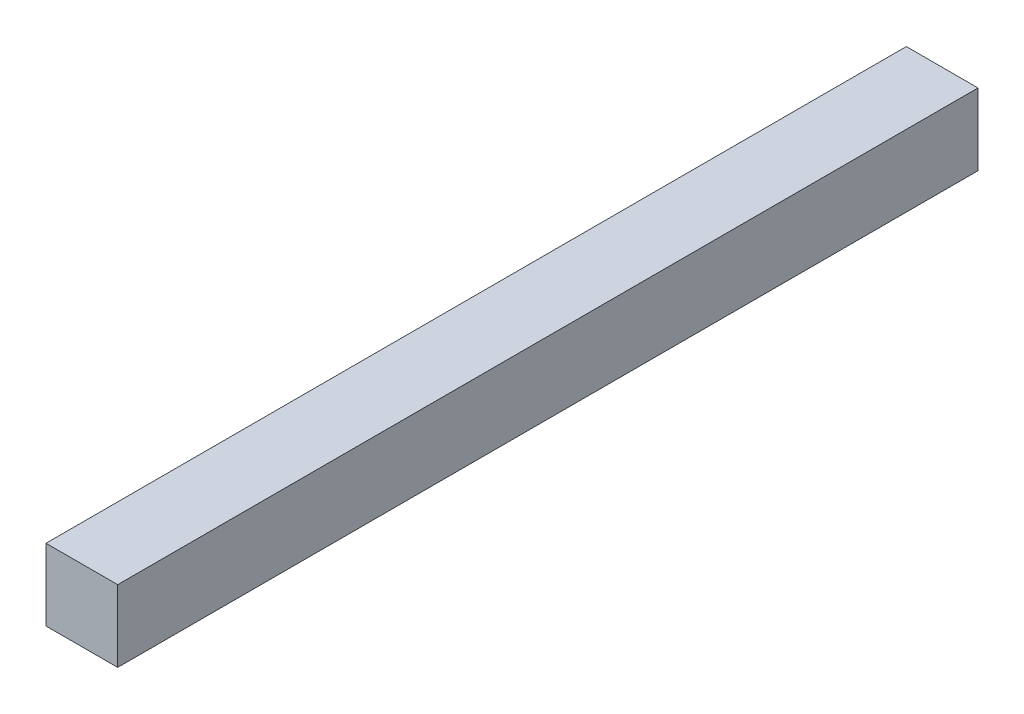
SolidWorks part; units mm, degrees
ref_plane "Front Plane" through (0, 0, 0) normal (0, 0, 1) x (1, 0, 0)
ref_plane "Top Plane" through (0, 0, 0) normal (0, 1, 0) x (1, 0, 0)
ref_plane "Right Plane" through (0, 0, 0) normal (1, 0, 0) x (0, 0, -1)
sketch "Sketch1" plane through (0, 0, 0) normal (0, 0, 1) x (1, 0, 0)
  line L1 (2.5, -2.5) -> (-2.5, -2.5)
  line L2 (2.5, -2.5) -> (2.5, 2.5)
  line L3 (2.5, 2.5) -> (-2.5, 2.5)
  line L4 (-2.5, -2.5) -> (-2.5, 2.5)
  line L5 (2.5, -2.5) -> (-2.5, 2.5) construction
  line L6 (2.5, 2.5) -> (-2.5, -2.5) construction
  point P0 (0, 0)
  dimension "D1" = 5
  dimension "D2" = 5
extrude "Boss-Extrude1" add sketch "Sketch1" along normal blind 60
